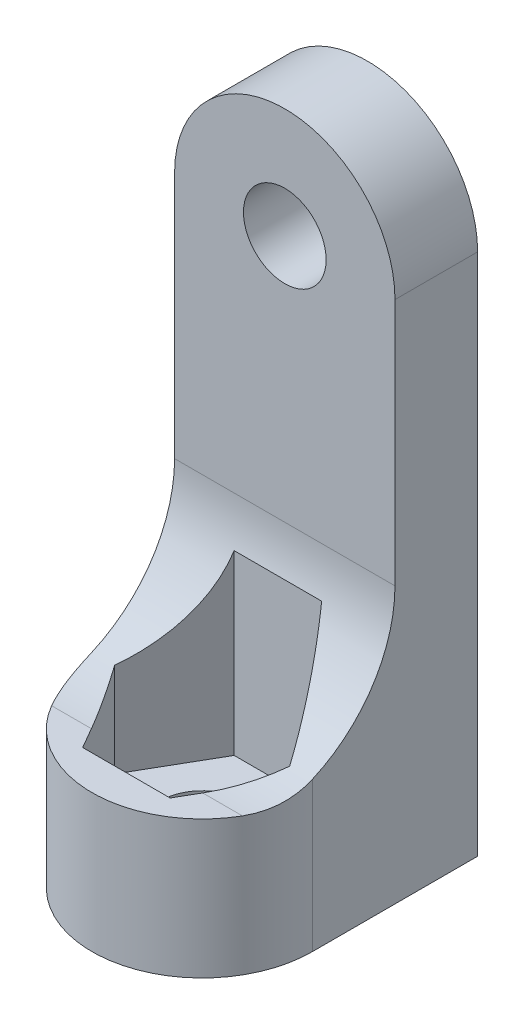
SolidWorks part; units mm, degrees
material "ABS"
ref_plane "Přední rovina" through (0, 0, 0) normal (0, 0, 1) x (1, 0, 0)
ref_plane "Horní rovina" through (0, 0, 0) normal (0, 1, 0) x (1, 0, 0)
ref_plane "Pravá rovina" through (0, 0, 0) normal (1, 0, 0) x (0, 0, -1)
sketch "Skica1" plane through (0, 0, 0) normal (0, 1, 0) x (1, 0, 0)
  line L0 (-4, 0) -> (-4, 6)
  line L1 (-4, 6) -> (4, 6)
  line L2 (4, 6) -> (4, 0)
  circle A0 centre (0, 0) radius 1.5
  arc A1 (-4, 0) -> (4, 0) centre (0, 0) ccw
  dimension "D1" = 3
  dimension "D2" = 8
  dimension "D3" = 10
extrude "Přidat vysunutím1" add sketch "Skica1" along normal blind 23
sketch "Skica2" plane through (-4, 0, 0) normal (-1, 0, 0) x (0, 0, 1)
  line L0 (-3, 23) -> (-3, 10)
  line L1 (-6, 23) -> (0, 23) construction
  line L2 (2, 5) -> (4, 5)
  line L3 (4, 0) -> (4, 23) construction
  line L4 (-3, 23) -> (-6, 23)
  line L5 (-6, 23) -> (-6, 0)
  line L6 (-6, 0) -> (4, 0)
  line L7 (0, 0) -> (4, 0) construction
  line L8 (4, 0) -> (4, 5)
  arc A0 (-3, 10) -> (2, 5) centre (2, 10) ccw
  point P17 (-3, 5)
  dimension "D4" = 5
  dimension "D1" = 5
  dimension "D3" = 3
extrude "Odebrat vysunutím2" cut sketch "Skica2" against normal through all flip side to cut
sketch "Skica3" plane through (0, 0, -6) normal (0, 0, -1) x (-1, 0, 0)
  line L0 (4, 23) -> (4, 0) construction
  line L3 (-4, 19) -> (-7.6022, 24.8748)
  line L4 (-7.6022, 24.8748) -> (9.8453, 23.958)
  line L5 (9.8453, 23.958) -> (4, 19)
  line L6 (-4, 23) -> (-4, 0) construction
  line L7 (-4, 23) -> (4, 23) construction
  arc A0 (-4, 19) -> (4, 19) centre (0, 19) cw
  circle A1 centre (0, 19) radius 1.5
  point P5 (0, 0)
  dimension "D1" = 3
extrude "Odebrat vysunutím3" cut sketch "Skica3" against normal through all
ref_plane "Rovina1" through (0, 2, 0) normal (0, -1, 0) x (1, 0, 0)
sketch "Skica6" plane through (0, 2, 0) normal (0, -1, 0) x (1, 0, 0)
  line L1 (1.5877, 2.75) -> (-1.5877, 2.75)
  line L2 (-1.5877, 2.75) -> (-3.1754, 0)
  line L3 (-3.1754, 0) -> (-1.5877, -2.75)
  line L4 (-1.5877, -2.75) -> (1.5877, -2.75)
  line L5 (1.5877, -2.75) -> (3.1754, 0)
  line L6 (3.1754, 0) -> (1.5877, 2.75)
  circle A0 centre (0, 0) radius 2.75 construction
  dimension "D1" = 5.5
extrude "Odebrat vysunutím4" cut sketch "Skica6" against normal through all
